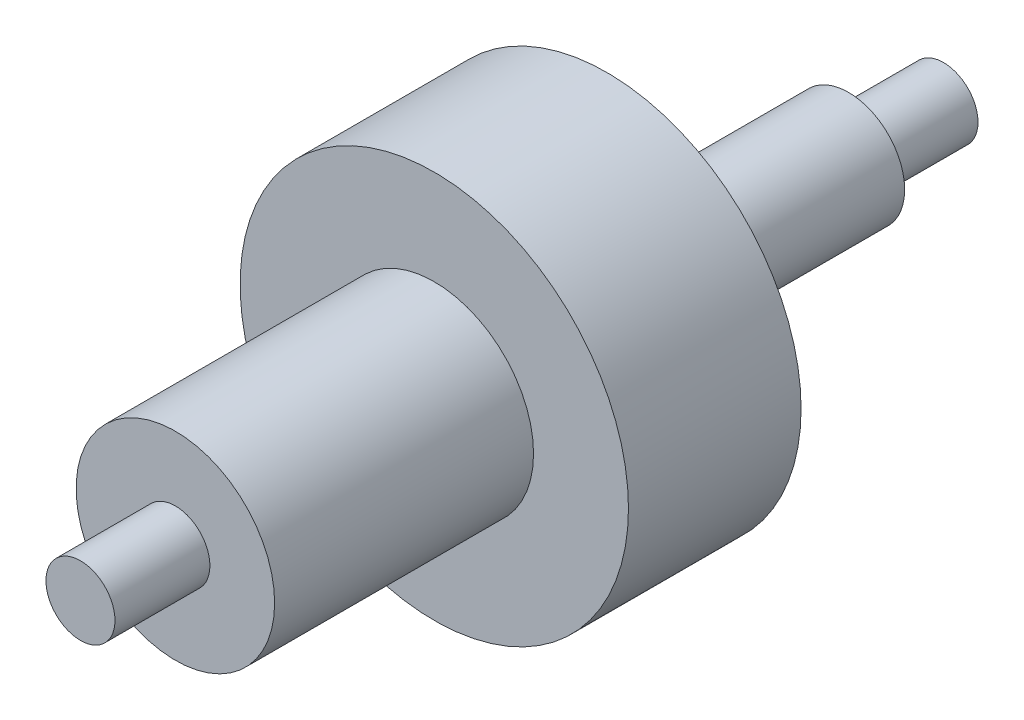
SolidWorks part; units mm, degrees
ref_plane "Front" through (0, 0, 0) normal (0, 0, 1) x (1, 0, 0)
ref_plane "Top" through (0, 0, 0) normal (0, 1, 0) x (1, 0, 0)
ref_plane "Right" through (0, 0, 0) normal (1, 0, 0) x (0, 0, -1)
sketch "Sketch1" plane through (0, 0, 0) normal (0, 0, 1) x (1, 0, 0)
  circle A0 centre (0, 0) radius 0.4
  dimension "D1" = 0.8
extrude "Boss-Extrude1" add sketch "Sketch1" along normal blind 1.1
sketch "Sketch2" plane through (0, 0, 1.1) normal (0, 0, 1) x (1, 0, 0)
  circle A0 centre (0, 0) radius 0.65
  dimension "D1" = 1.3
extrude "Boss-Extrude2" add sketch "Sketch2" along normal blind 2.8
sketch "Sketch3" plane through (0, 0, 3.9) normal (0, 0, 1) x (1, 0, 0)
  circle A0 centre (0, 0) radius 2.25
  dimension "D1" = 4.5
extrude "Boss-Extrude3" add sketch "Sketch3" along normal blind 2
sketch "Sketch4" plane through (0, 0, 5.9) normal (0, 0, 1) x (1, 0, 0)
  circle A0 centre (0, 0) radius 1.15
  dimension "D1" = 2.3
extrude "Boss-Extrude4" add sketch "Sketch4" along normal blind 3
sketch "Sketch5" plane through (0, 0, 8.9) normal (0, 0, 1) x (1, 0, 0)
  circle A0 centre (0, 0) radius 0.4
  dimension "D1" = 0.8
extrude "Boss-Extrude5" add sketch "Sketch5" along normal blind 1.1
